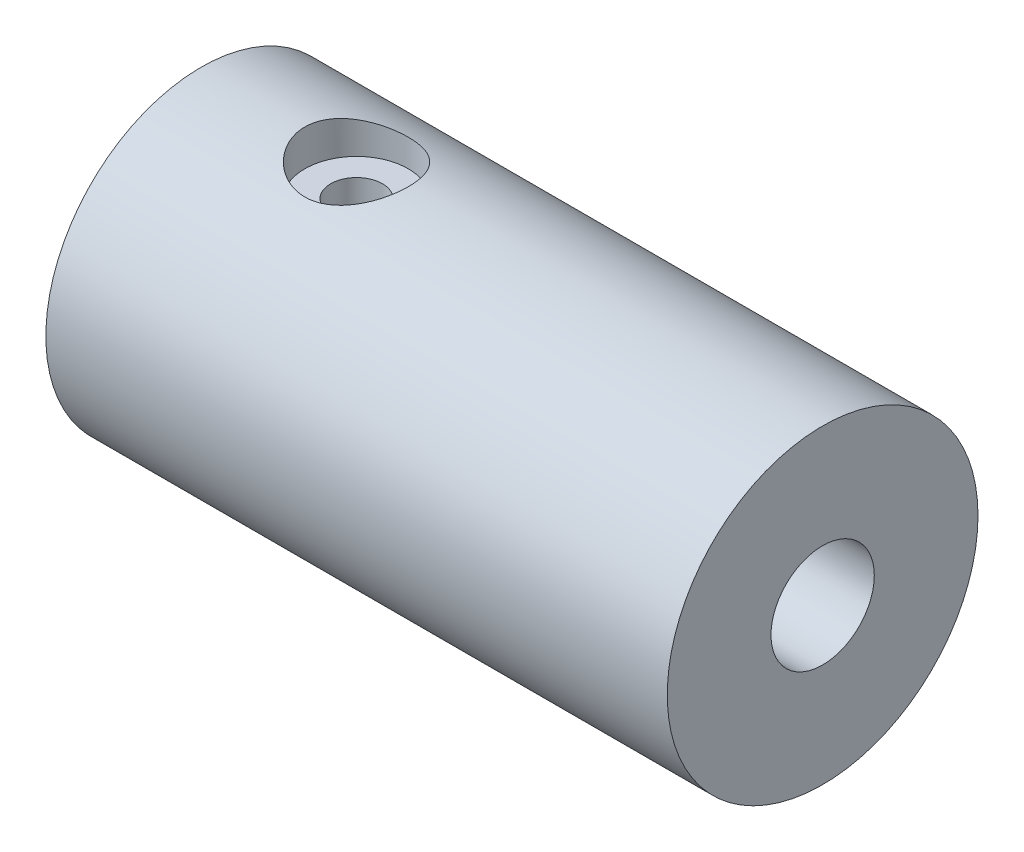
SolidWorks part; units mm, degrees
ref_plane "Front Plane" through (0, 0, 0) normal (0, 0, 1) x (1, 0, 0)
ref_plane "Top Plane" through (0, 0, 0) normal (0, 1, 0) x (1, 0, 0)
ref_plane "Right Plane" through (0, 0, 0) normal (1, 0, 0) x (0, 0, -1)
sketch "Sketch1" plane through (0, 0, 0) normal (1, 0, 0) x (0, 0, -1)
  circle A0 centre (0, 0) radius 3
  dimension "D1" = 6
extrude "Boss-Extrude1" add sketch "Sketch1" along normal blind 12
sketch "Sketch2" plane through (0, 0, 0) normal (1, 0, 0) x (0, 0, -1)
  circle A0 centre (0, 0) radius 1.095
  dimension "D1" = 2.19
extrude "Cut-Extrude1" cut sketch "Sketch2" along normal blind 7
ref_plane "Plane1" through (0, 3, 0) normal (0, 1, 0) x (1, 0, 0)
sketch "Sketch3" plane through (0, 3, 0) normal (0, 1, 0) x (1, 0, 0)
  line L0 (3, -4.6736) -> (3, 4.4372)
  line L1 (0, 0) -> (5.4843, 0)
  circle A0 centre (3, 0) radius 1
  point P7 (3, -0.1182)
  dimension "D2" = 2
  dimension "D1" = 3
extrude "Cut-Extrude2" cut sketch "Sketch3" against normal blind 0.7 contours A0
ref_plane "Plane2" through (0, 2.65, 0) normal (0, 1, 0) x (1, 0, 0)
sketch "Sketch4" plane through (0, 2.65, 0) normal (0, 1, 0) x (1, 0, 0)
  circle A0 centre (3, 0) radius 0.5
  dimension "D1" = 1
extrude "Cut-Extrude3" cut sketch "Sketch4" against normal up to next
ref_plane "Plane3" through (12, 0, 0) normal (1, 0, 0) x (0, 0, -1)
sketch "Sketch5" plane through (12, 0, 0) normal (1, 0, 0) x (0, 0, -1)
  circle A0 centre (0, 0) radius 0.9975
  dimension "D1" = 1.995
extrude "Cut-Extrude4" cut sketch "Sketch5" against normal blind 3
